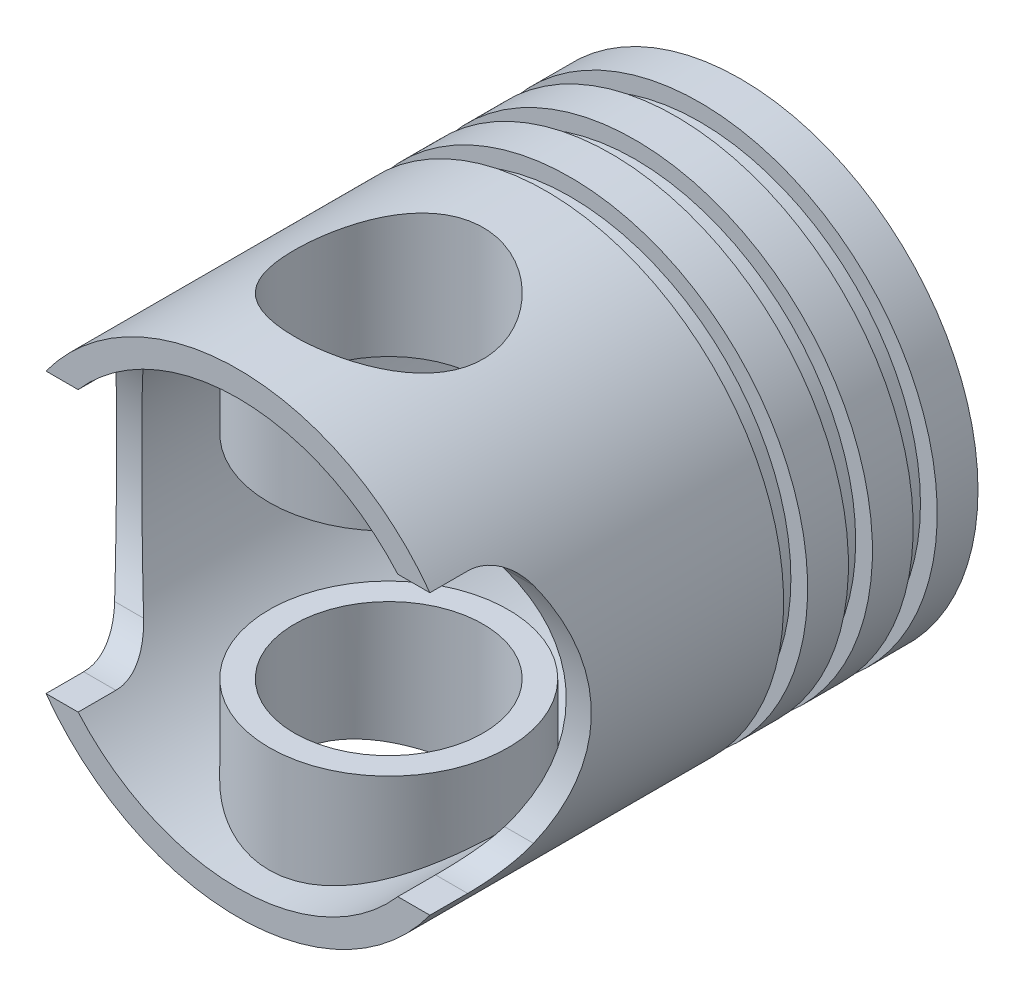
SolidWorks part; units mm, degrees
ref_plane "Front Plane" through (0, 0, 0) normal (0, 0, 1) x (1, 0, 0)
ref_plane "Top Plane" through (0, 0, 0) normal (0, 1, 0) x (1, 0, 0)
ref_plane "Right Plane" through (0, 0, 0) normal (1, 0, 0) x (0, 0, -1)
sketch "Sketch2" plane through (0, 0, 0) normal (0, 1, 0) x (1, 0, 0)
  line L0 (0, 0) -> (-42.5, 0)
  line L1 (-42.5, 0) -> (-42.5, 55.2)
  line L3 (0, 90) -> (0, 0)
  line L4 (-42.5, 82.7) -> (-39.5, 82.7)
  line L5 (0, 90) -> (0, 95)
  line L6 (-42.5, 78.4) -> (-39.5, 78.4)
  line L7 (-42.5, 66.8) -> (-39.5, 66.8)
  line L8 (-42.5, 71.1) -> (-39.5, 71.1)
  line L9 (-42.5, 78.4) -> (-39.5, 78.4)
  line L10 (-42.5, 55.2) -> (-39.5, 55.2)
  line L11 (-42.5, 59.5) -> (-39.5, 59.5)
  line L12 (-42.5, 66.8) -> (-39.5, 66.8)
  line L13 (-42.5, 0) -> (-39.5, 0)
  line L14 (-39.5, 55.2) -> (-39.5, 59.5)
  line L17 (-42.5, 82.7) -> (-42.5, 90)
  line L18 (-42.5, 71.1) -> (-42.5, 78.4)
  line L19 (-42.5, 59.5) -> (-42.5, 66.8)
  line L20 (-39.5, 66.8) -> (-39.5, 71.1)
  line L21 (-39.5, 78.4) -> (-39.5, 82.7)
  arc A0 (0, 95) -> (-42.5, 90) centre (0, -88.125) ccw
revolve "Revolve1" add sketch "Sketch2" angle 360 about L3
sketch "Sketch3" plane through (0, 0, 0) normal (0, 1, 0) x (1, 0, 0)
  line L0 (0, 0) -> (0, 27)
  circle A0 centre (0, 27) radius 16.9
extrude "Cut-Extrude1" cut sketch "Sketch3" against normal through all and the other way through all
sketch "Sketch4" plane through (0, 0, 0) normal (0, 0, 1) x (1, 0, 0)
  circle A0 centre (0, 0) radius 38
extrude "Cut-Extrude2" cut sketch "Sketch4" against normal blind 85
sketch "Sketch5" plane through (0, 0, 0) normal (0, 1, 0) x (1, 0, 0)
  circle A0 centre (0, 27) radius 16.9
  circle A1 centre (0, 27) radius 21.4
extrude "Boss-Extrude2" add sketch "Sketch5" along normal up to next from offset 19
mirror "Mirror1" about plane through (0, 0, 0) normal (0, 1, 0) of "Boss-Extrude2"
sketch "Sketch6" plane through (0, 0, 0) normal (1, 0, 0) x (0, 0, -1)
  line L0 (0, -25) -> (0, 25)
  line L1 (0, 42.5) -> (0, -42.5) construction
  line L3 (0, 25) -> (6.7558, 25)
  line L4 (0, -25) -> (6.7558, -25)
  arc A1 (15.416, 20) -> (15.416, -20) centre (-19.225, 0) cw
  arc A2 (6.7558, -25) -> (15.416, -20) centre (6.7558, -15) ccw
  arc A3 (6.7558, 25) -> (15.416, 20) centre (6.7558, 15) cw
  point P6 (0, 0)
  dimension "D1" = 10
extrude "Cut-Extrude3" cut sketch "Sketch6" against normal through all from offset 25 offset against normal yes
mirror "Mirror2" about plane through (0, 0, 0) normal (1, 0, 0) of "Cut-Extrude3"
